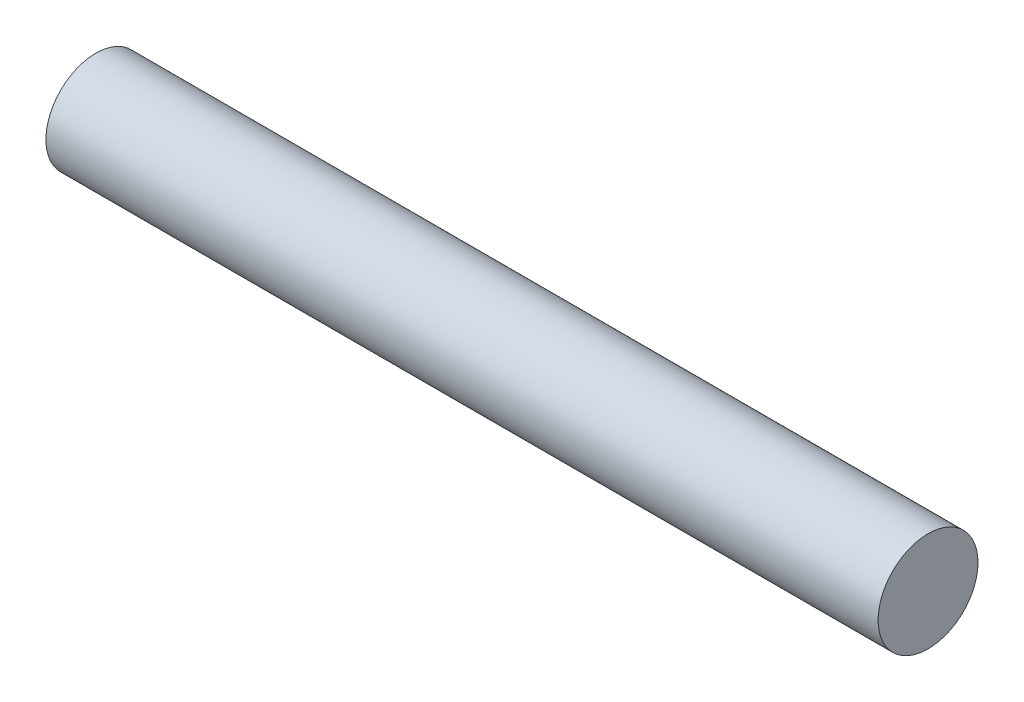
SolidWorks part; units mm, degrees
ref_plane "Front Plane" through (0, 0, 0) normal (0, 0, 1) x (1, 0, 0)
ref_plane "Top Plane" through (0, 0, 0) normal (0, 1, 0) x (1, 0, 0)
ref_plane "Right Plane" through (0, 0, 0) normal (1, 0, 0) x (0, 0, -1)
sketch "Sketch1" plane through (0, 0, 0) normal (1, 0, 0) x (0, 0, -1)
  circle A0 centre (0, 0) radius 3
  dimension "D1" = 6
extrude "Boss-Extrude1" add sketch "Sketch1" along normal blind 50
